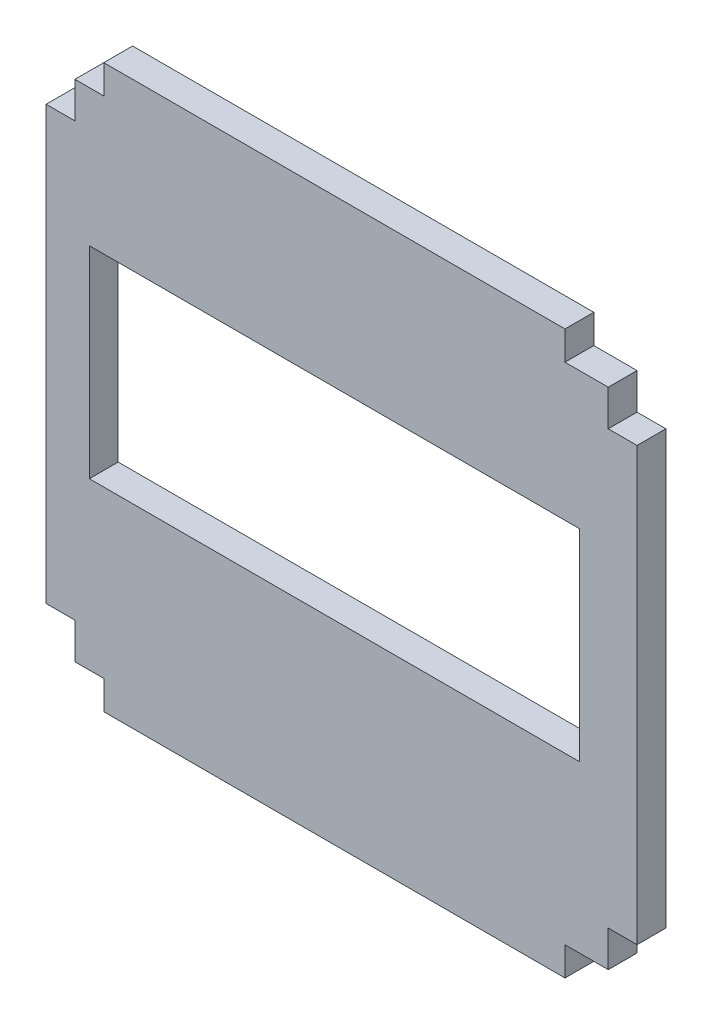
SolidWorks part; units mm, degrees
ref_plane "前视基准面" through (0, 0, 0) normal (0, 0, 1) x (1, 0, 0)
ref_plane "上视基准面" through (0, 0, 0) normal (0, 1, 0) x (1, 0, 0)
ref_plane "右视基准面" through (0, 0, 0) normal (1, 0, 0) x (0, 0, -1)
sketch "草图1" plane through (0, 0, 0) normal (0, 0, 1) x (1, 0, 0)
  line L0 (0, -35) -> (2, -35)
  line L5 (2, -35) -> (2, -37)
  line L6 (37, -35) -> (34, -35)
  line L11 (2, -37) -> (34, -37)
  line L12 (34, -37) -> (34, -35)
  line L18 (0, -35) -> (0, -32.5)
  line L19 (0, -32.5) -> (-2, -32.5)
  line L24 (-2, -2.5) -> (-2, -32.5)
  line L30 (37, -32.5) -> (39, -32.5)
  line L31 (39, -32.5) -> (39, -2.5)
  line L33 (37, -32.5) -> (37, -35)
  line L34 (37, -2.5) -> (37, 0)
  line L35 (37, -2.5) -> (39, -2.5)
  line L36 (0, -2.5) -> (-2, -2.5)
  line L37 (0, 0) -> (0, -2.5)
  line L38 (34, 2) -> (34, 0)
  line L39 (2, 2) -> (34, 2)
  line L41 (37, 0) -> (34, 0)
  line L42 (2, 0) -> (2, 2)
  line L43 (0, 0) -> (2, 0)
  line L53 (18, -23.5) -> (2.5, -23.5)
  line L54 (18, -23.5) -> (33.5, -23.5)
  line L56 (35, -11.5) -> (35, -23.5)
  line L57 (35, -23.5) -> (33.5, -23.5)
  line L59 (1, -11.5) -> (1, -23.5)
  line L60 (1, -23.5) -> (2.5, -23.5)
  line L61 (35, -11.5) -> (35, -9.5)
  line L62 (35, -9.5) -> (1, -9.5)
  line L63 (1, -9.5) -> (1, -11.5)
  point P24 (2, -17.5)
  point P26 (18, -17.5)
extrude "凸台-拉伸1" add sketch "草图1" along normal blind 2
